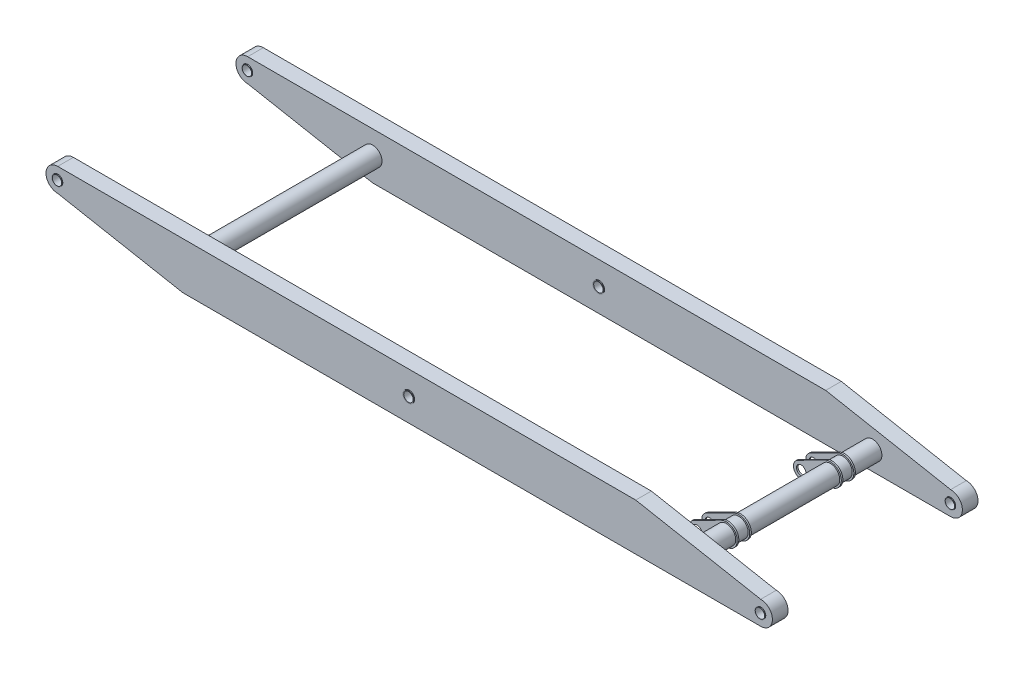
SolidWorks part; units mm, degrees
ref_plane "前视基准面" through (0, 0, 0) normal (0, 0, 1) x (1, 0, 0)
ref_plane "上视基准面" through (0, 0, 0) normal (0, 1, 0) x (1, 0, 0)
ref_plane "右视基准面" through (0, 0, 0) normal (1, 0, 0) x (0, 0, -1)
sketch "草图1" plane through (0, 0, 0) normal (0, 0, 1) x (1, 0, 0)
  line L0 (-60.1324, -127.5332) -> (739.8676, -277.5332)
  line L1 (-60.1324, 22.4668) -> (3639.8676, 22.4668)
  line L3 (739.8676, -277.5332) -> (4439.8676, -277.5332)
  line L5 (4439.8676, -127.5332) -> (3639.8676, 22.4668)
  arc A0 (-60.1324, 22.4668) -> (-60.1324, -127.5332) centre (-60.1324, -52.5332) ccw
  arc A1 (4439.8676, -277.5332) -> (4439.8676, -127.5332) centre (4439.8676, -202.5332) ccw
extrude "凸台-拉伸1" add sketch "草图1" along normal blind 100
sketch "草图2" plane through (0, 0, 100) normal (0, 0, 1) x (1, 0, 0)
  circle A0 centre (-60.1324, -52.5332) radius 30
  circle A1 centre (4439.8676, -202.5332) radius 30
extrude "切除-拉伸1" cut sketch "草图2" against normal blind 100
sketch "草图3" plane through (0, 0, 0) normal (0, 0, -1) x (-1, 0, 0)
  circle A0 centre (-4439.8676, -202.5332) radius 30
  circle A1 centre (-4439.8676, -202.5332) radius 32.5
  circle A2 centre (60.1324, -52.5332) radius 30
  circle A3 centre (60.1324, -52.5332) radius 32.5
extrude "凸台-拉伸2" add sketch "草图3" along normal blind 5
sketch "草图4" plane through (0, 0, 100) normal (0, 0, 1) x (1, 0, 0)
  circle A0 centre (-60.1324, -52.5332) radius 30 construction
  circle A1 centre (-60.1324, -52.5332) radius 32.5
  circle A2 centre (-60.1324, -52.5332) radius 32.5
  circle A3 centre (-60.1324, -52.5332) radius 30
  circle A4 centre (4439.8676, -202.5332) radius 32.5 construction
  circle A5 centre (4439.8676, -202.5332) radius 32.5
  circle A6 centre (4439.8676, -202.5332) radius 30 construction
  circle A7 centre (4439.8676, -202.5332) radius 30
  dimension "D1" = 0
extrude "凸台-拉伸3" add sketch "草图4" along normal blind 5
sketch "草图5" plane through (0, 0, 0) normal (0, 0, -1) x (-1, 0, 0)
  circle A0 centre (-2189.8676, -127.5332) radius 30
extrude "切除-拉伸2" cut sketch "草图5" against normal blind 248
sketch "草图6" plane through (0, 0, 0) normal (0, 0, -1) x (-1, 0, 0)
  circle A0 centre (-2189.8676, -127.5332) radius 35
  circle A1 centre (-2189.8676, -127.5332) radius 30
extrude "凸台-拉伸4" add sketch "草图6" along normal blind 5
sketch "草图7" plane through (0, 0, 100) normal (0, 0, 1) x (1, 0, 0)
  circle A0 centre (2189.8676, -127.5332) radius 35 construction
  circle A1 centre (2189.8676, -127.5332) radius 35
  circle A2 centre (2189.8676, -127.5332) radius 30 construction
  circle A3 centre (2189.8676, -127.5332) radius 30
extrude "凸台-拉伸5" add sketch "草图7" along normal blind 5
sketch "草图8" plane through (0, 0, 100) normal (0, 0, 1) x (1, 0, 0)
  circle A0 centre (739.8676, -127.5332) radius 60
extrude "凸台-拉伸6" add sketch "草图8" along normal blind 558
mirror "镜向1" about plane through (739.8676, -127.5332, 658) normal (0, 0, 1) of bodies 108
sketch "草图9" plane through (0, 0, 1216) normal (0, 0, -1) x (-1, 0, 0)
  line L0 (-739.8676, -277.5332) -> (-4439.8676, -277.5332) construction
  circle A0 centre (-3939.8676, -157.5332) radius 60
  circle A1 centre (-4439.8676, -202.5332) radius 32.5 construction
  dimension "D1" = 500
  dimension "D2" = 120
extrude "凸台-拉伸7" add sketch "草图9" along normal up to surface (1116 mm away) up to face at (2224.8676, -127.5332, 100)
ref_plane "基准面1" through (0, 0, 658) normal (0, 0, -1) x (-1, 0, 0)
ref_plane "基准面3" through (0, 0, 370) normal (0, 0, -1) x (-1, 0, 0)
sketch "草图12" plane through (0, 0, 370) normal (0, 0, -1) x (-1, 0, 0)
  line L2 (-3921.5516, -88.3791) -> (-3730.6551, -184.5536)
  line L3 (-3958.2926, -225.0649) -> (-3766.3122, -277.4437)
  arc A0 (-3908.3726, -95.0188) -> (-3958.2926, -225.0649) centre (-3939.8676, -157.5332) ccw
  arc A1 (-3766.3122, -277.4437) -> (-3730.6551, -184.5536) centre (-3753.1516, -229.2068) ccw
  circle A2 centre (-3753.1516, -229.2068) radius 30
  dimension "D2" = 100
  dimension "D3" = 140
  dimension "D4" = 200
extrude "凸台-拉伸9" add sketch "草图12" along normal blind 10 contours L3 A1 L2 A0 A2
pattern_linear "阵列(线性)2" count 2 spacing 80 along (0, 0, -1) of "凸台-拉伸9"
mirror "镜向3" about plane through (0, 0, 658) normal (0, 0, -1) of "阵列(线性)2", "凸台-拉伸9"
scale "Scale1" scale about centroid uniform scaling yes scale factor 0.345
